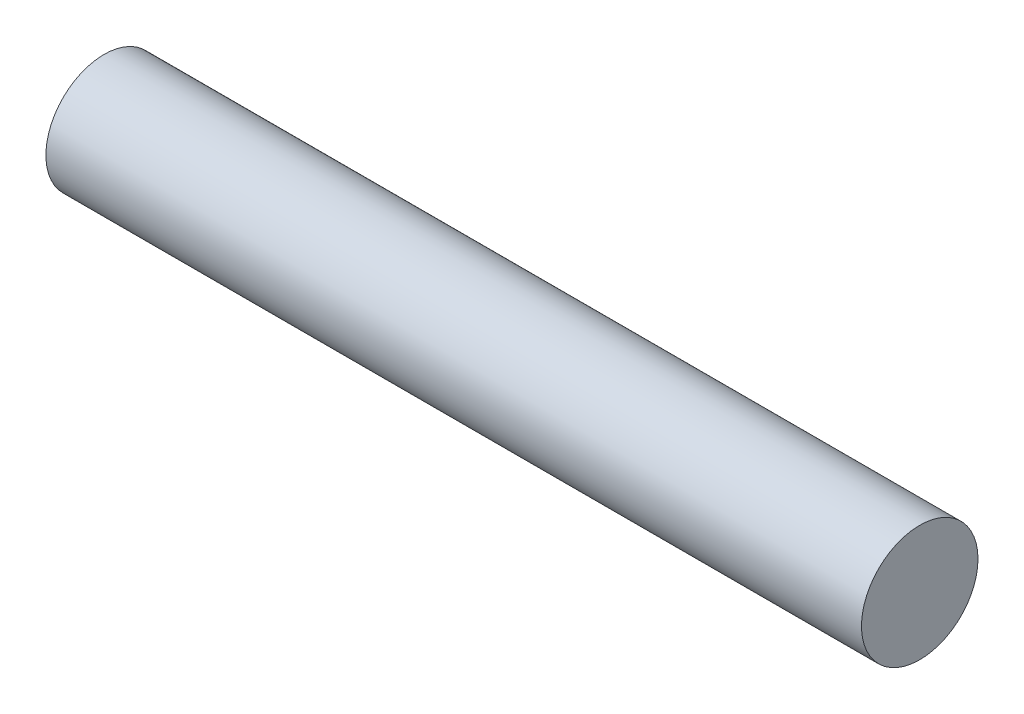
SolidWorks part; units mm, degrees
ref_plane "Front Plane" through (0, 0, 0) normal (0, 0, 1) x (1, 0, 0)
ref_plane "Top Plane" through (0, 0, 0) normal (0, 1, 0) x (1, 0, 0)
ref_plane "Right Plane" through (0, 0, 0) normal (1, 0, 0) x (0, 0, -1)
sketch "Sketch1" plane through (0, 0, 0) normal (1, 0, 0) x (0, 0, -1)
  circle A0 centre (0, 0) radius 7.5
  dimension "D1" = 15
extrude "Boss-Extrude1" add sketch "Sketch1" along normal blind 105
